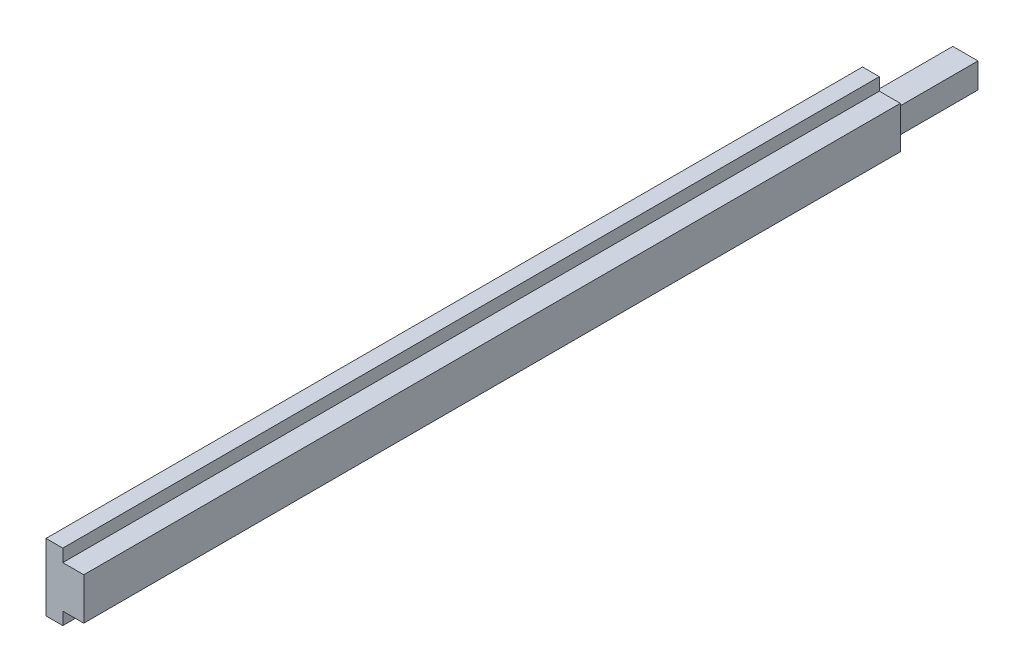
SolidWorks part; units mm, degrees
ref_plane "Front Plane" through (0, 0, 0) normal (1, 0, 0) x (0, 1, 0)
ref_plane "Top Plane" through (0, 0, 0) normal (0, 0, 1) x (0, 1, 0)
ref_plane "Right Plane" through (0, 0, 0) normal (0, 1, 0) x (-1, 0, 0)
sketch "Sketch1" plane through (0, 0, 0) normal (0, 0, 1) x (0, 1, 0)
  line L1 (-8, -2) -> (8, -2)
  line L2 (-8, -2) -> (-8, 2)
  line L3 (-8, 2) -> (8, 2)
  line L4 (8, -2) -> (8, 2)
  line L5 (-8, -2) -> (8, 2) construction
  line L6 (-8, 2) -> (8, -2) construction
  line L7 (-5, -2) -> (5, -2)
  line L8 (-5, -2) -> (-5, -7)
  line L9 (-5, -7) -> (5, -7)
  line L10 (5, -2) -> (5, -7)
  point P0 (0, 0)
  dimension "D1" = 9
  dimension "D2" = 4
  dimension "D3" = 16
  dimension "D4" = 10
  dimension "D5" = 3
extrude "Boss-Extrude1" add sketch "Sketch1" against normal blind 194.5 contours L10 L1 L8 L9 | L1 L4 L3 L2
sketch "Sketch2" plane through (0, 0, -194.5) normal (0, 0, -1) x (1, 0, 0)
  line L0 (0, 0) -> (2.5, 0) construction
  line L1 (-0.5, -3) -> (5.5, -3)
  line L2 (-0.5, -3) -> (-0.5, 3)
  line L3 (-0.5, 3) -> (5.5, 3)
  line L4 (5.5, -3) -> (5.5, 3)
  line L5 (-0.5, -3) -> (5.5, 3) construction
  line L6 (-0.5, 3) -> (5.5, -3) construction
  line L7 (-2, 8) -> (-2, -8) construction
  point P0 (2.5, 0)
  dimension "D1" = 6
  dimension "D2" = 6
  dimension "D3" = 4.5
extrude "Boss-Extrude2" add sketch "Sketch2" along normal blind 20
equation "\"CD_Height\"= 125mm"
equation "\"CD_Thickness\"= 10mm"
equation "\"CD_Width\"= 142mm"
equation "\"Wall_Thickness\"= 10mm"
equation "\"Total_Height\"= 3 * \"CD_Height\" + 2 * \"Wall_Thickness\" + 4mm"
equation "\"Total_Width\"= \"CD_Width\" * 3 + \"Wall_Thickness\" * 2 + 4mm"
equation "\"Tolerance\"= 1mm"
equation "\"Overhang_Width\"= 10mm"
equation "\"D1@Sketch1\"=\"Wall_Thickness\"-1"
equation "\"D2@Sketch1\"=\"Wall_Thickness\"/2-1mm"
equation "\"D3@Sketch1\"=\"Wall_Thickness\"+6mm"
equation "\"D4@Sketch1\"=\"Wall_Thickness\""
equation "\"D1@Boss-Extrude1\"=(\"Total_Height\"-\"Wall_Thickness\")/2"
equation "\"D1@Sketch2\"=\"Wall_Thickness\"-4mm"
equation "\"D2@Sketch2\"=\"Wall_Thickness\"-4mm"
equation "\"D3@Sketch2\"=(\"Wall_Thickness\"-1mm)/2"
